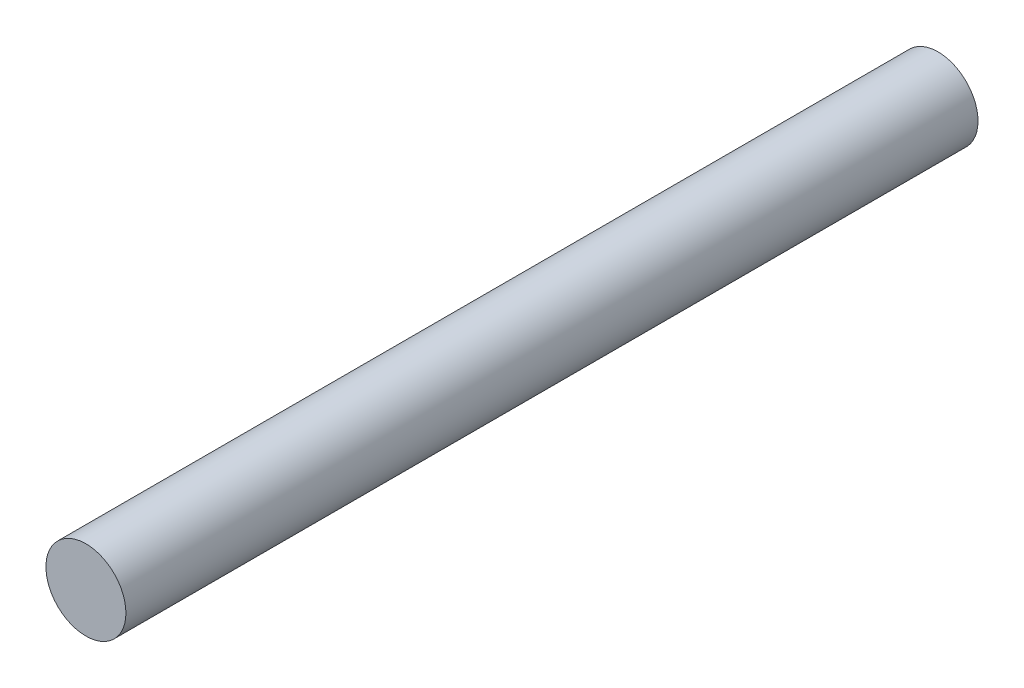
SolidWorks part; units mm, degrees
material "6061-T6 (SS)"
ref_plane "Front Plane" through (0, 0, 0) normal (0, 0, 1) x (1, 0, 0)
ref_plane "Top Plane" through (0, 0, 0) normal (0, 1, 0) x (1, 0, 0)
ref_plane "Right Plane" through (0, 0, 0) normal (1, 0, 0) x (0, 0, -1)
sketch "Sketch1" plane through (0, 0, 0) normal (0, 0, 1) x (1, 0, 0)
  circle A0 centre (0, 0) radius 4.7625
  dimension "D1" = 9.525
extrude "Boss-Extrude1" add sketch "Sketch1" along normal blind 101.473
